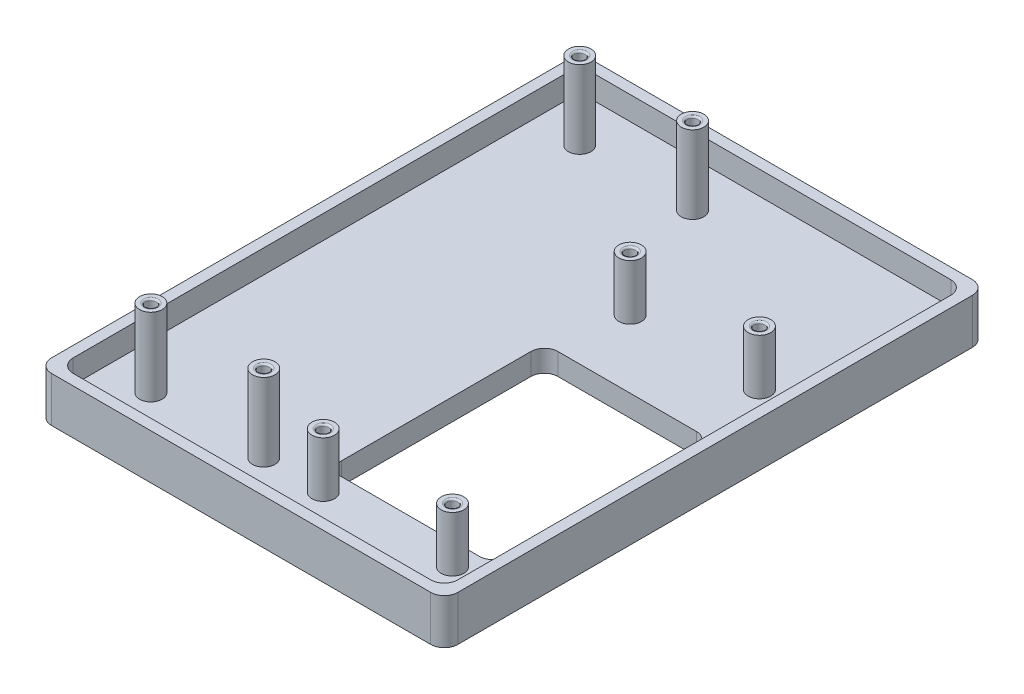
SolidWorks part; units mm, degrees
ref_plane "Alzado" through (0, 0, 0) normal (0, 0, 1) x (1, 0, 0)
ref_plane "Planta" through (0, 0, 0) normal (0, 1, 0) x (1, 0, 0)
ref_plane "Vista lateral" through (0, 0, 0) normal (1, 0, 0) x (0, 0, -1)
sketch "Croquis1" plane through (0, 0, 0) normal (0, 1, 0) x (1, 0, 0)
  line L1 (45, -60) -> (-45, -60)
  line L2 (45, -60) -> (45, 60)
  line L3 (45, 60) -> (-45, 60)
  line L4 (-45, -60) -> (-45, 60)
  line L5 (45, -60) -> (-45, 60) construction
  line L6 (45, 60) -> (-45, -60) construction
  point P0 (0, 0)
  dimension "D1" = 90
  dimension "D2" = 120
extrude "Saliente-Extruir1" add sketch "Croquis1" along normal blind 10
sketch "Croquis2" plane through (0, 10, 0) normal (0, 1, 0) x (1, 0, 0)
  line L0 (45, 60) -> (-45, 60) construction
  line L1 (42.6, -57.6) -> (-42.6, -57.6)
  line L2 (42.6, -57.6) -> (42.6, 57.6)
  line L3 (42.6, 57.6) -> (-42.6, 57.6)
  line L4 (-42.6, -57.6) -> (-42.6, 57.6)
  line L5 (42.6, -57.6) -> (-42.6, 57.6) construction
  line L6 (42.6, 57.6) -> (-42.6, -57.6) construction
  line L7 (-45, 60) -> (-45, -60) construction
  point P0 (0, 0)
  dimension "D1" = 2.4
  dimension "D2" = 2.4
extrude "Cortar-Extruir1" cut sketch "Croquis2" against normal blind 5.2
fillet "Redondeo1" radius 3 8 edges at (-42.6, 7.4, 57.6) (-42.6, 7.4, -57.6) (42.6, 7.4, -57.6) (42.6, 7.4, 57.6) (-45, 5, -60) (45, 5, -60) (45, 5, 60) (-45, 5, 60)
sketch "Croquis3" plane through (0, 4.8, 0) normal (0, 1, 0) x (1, 0, 0)
  line L0 (0, 0) -> (0, 55) construction
  line L1 (0, 55) -> (40, 55) construction
  line L2 (40, 55) -> (40, 0) construction
  line L3 (40, 0) -> (0, 0) construction
  line L4 (0, 55) -> (-40, 55) construction
  line L5 (-40, 55) -> (-40, -55) construction
  line L6 (-40, -55) -> (40, -55) construction
  line L7 (40, -55) -> (40, 0) construction
  line L8 (-40, 49.5) -> (0, 49.5) construction
  line L9 (-34.5, 55) -> (-34.5, -55) construction
  circle A0 centre (-32.5, 47.5) radius 2.5
  circle A1 centre (-7.5, 47.5) radius 2.5
  circle A2 centre (-7.5, -47.5) radius 2.5
  circle A3 centre (-32.5, -47.5) radius 2.5
  dimension "D7" = 5
  dimension "D1" = 40
  dimension "D2" = 110
  dimension "D3" = 40
  dimension "D4" = 55
  dimension "D5" = 5.5
  dimension "D6" = 5.5
  dimension "D8" = 2
  dimension "D9" = 2
  dimension "D11" = 25
  dimension "D12" = 95
  dimension "D13" = 7.5
  dimension "D10" = 2
extrude "Saliente-Extruir2" add sketch "Croquis3" along normal blind 17.2
sketch "Croquis4" plane through (0, 22, 0) normal (0, 1, 0) x (1, 0, 0)
  circle A0 centre (-32.5, 47.5) radius 1.2
  circle A1 centre (-7.5, 47.5) radius 1.2
  circle A2 centre (-7.5, -47.5) radius 1.2
  circle A3 centre (-32.5, -47.5) radius 1.2
  dimension "D1" = 2.4
  dimension "D2" = 2
extrude "Cortar-Extruir2" cut sketch "Croquis4" against normal blind 5
fillet "Redondeo2" radius 0.4 4 edges at (-32.5, 22, 48.7) (-7.5, 22, 48.7) (-7.5, 22, -46.3) (-32.5, 22, -46.3)
sketch "Croquis5" plane through (0, 4.8, 0) normal (0, 1, 0) x (1, 0, 0)
  line L0 (0, 0) -> (40, 0) construction
  line L1 (40, 0) -> (40, 55) construction
  line L2 (40, 55) -> (0, 55) construction
  line L3 (0, 55) -> (0, 0) construction
  line L4 (0, 0) -> (0, -55) construction
  line L5 (0, -55) -> (40, -55) construction
  line L6 (40, -55) -> (40, 0) construction
  line L7 (3.68, -55) -> (3.68, -49.5) construction
  line L8 (3.68, -49.5) -> (0, -49.5) construction
  circle A0 centre (5.68, -47.5) radius 2.5
  circle A1 centre (34.32, -47.5) radius 2.5
  circle A2 centre (34.32, 20.5) radius 2.5
  circle A3 centre (5.68, 20.5) radius 2.5
  dimension "D4" = 3.68
  dimension "D6" = 5
  dimension "D1" = 40
  dimension "D2" = 110
  dimension "D3" = 55
  dimension "D5" = 5.5
  dimension "D7" = 2
  dimension "D8" = 2
  dimension "D10" = 28.64
  dimension "D11" = 68
  dimension "D9" = 2
extrude "Saliente-Extruir3" add sketch "Croquis5" along normal blind 12.2
sketch "Croquis6" plane through (0, 17, 0) normal (0, 1, 0) x (1, 0, 0)
  circle A0 centre (5.68, -47.5) radius 1.2
  circle A1 centre (34.32, -47.5) radius 1.2
  circle A2 centre (34.32, 20.5) radius 1.2
  circle A3 centre (5.68, 20.5) radius 1.2
  dimension "D1" = 2.4
  dimension "D2" = 2
extrude "Cortar-Extruir3" cut sketch "Croquis6" against normal blind 5
fillet "Redondeo3" radius 0.4 4 edges at (34.32, 17, -19.3) (5.68, 17, -19.3) (34.32, 17, 48.7) (5.68, 17, 48.7)
sketch "Croquis7" plane through (0, 4.8, 0) normal (0, 1, 0) x (1, 0, 0)
  line L0 (5.68, 20.5) -> (34.32, 20.5) construction
  line L1 (34.32, 20.5) -> (34.32, -47.5) construction
  line L2 (34.32, -47.5) -> (5.68, -47.5) construction
  line L3 (5.68, -47.5) -> (5.68, 20.5) construction
  line L5 (1.68, 5.5) -> (38.32, 5.5)
  line L6 (1.68, 5.5) -> (1.68, -42.5)
  line L7 (1.68, -42.5) -> (38.32, -42.5)
  line L8 (38.32, 5.5) -> (38.32, -42.5)
  line L9 (1.68, 5.5) -> (38.32, -42.5) construction
  line L10 (1.68, -42.5) -> (38.32, 5.5) construction
  point P12 (20, -18.5)
  dimension "D1" = 15
  dimension "D2" = 5
  dimension "D3" = 4
  dimension "D4" = 4
extrude "Cortar-Extruir4" cut sketch "Croquis7" against normal up to surface (4.8 mm away) up to face at (0, 0, 0)
fillet "Redondeo4" radius 3 4 edges at (1.68, 2.4, 42.5) (38.32, 2.4, 42.5) (1.68, 2.4, -5.5) (38.32, 2.4, -5.5)
